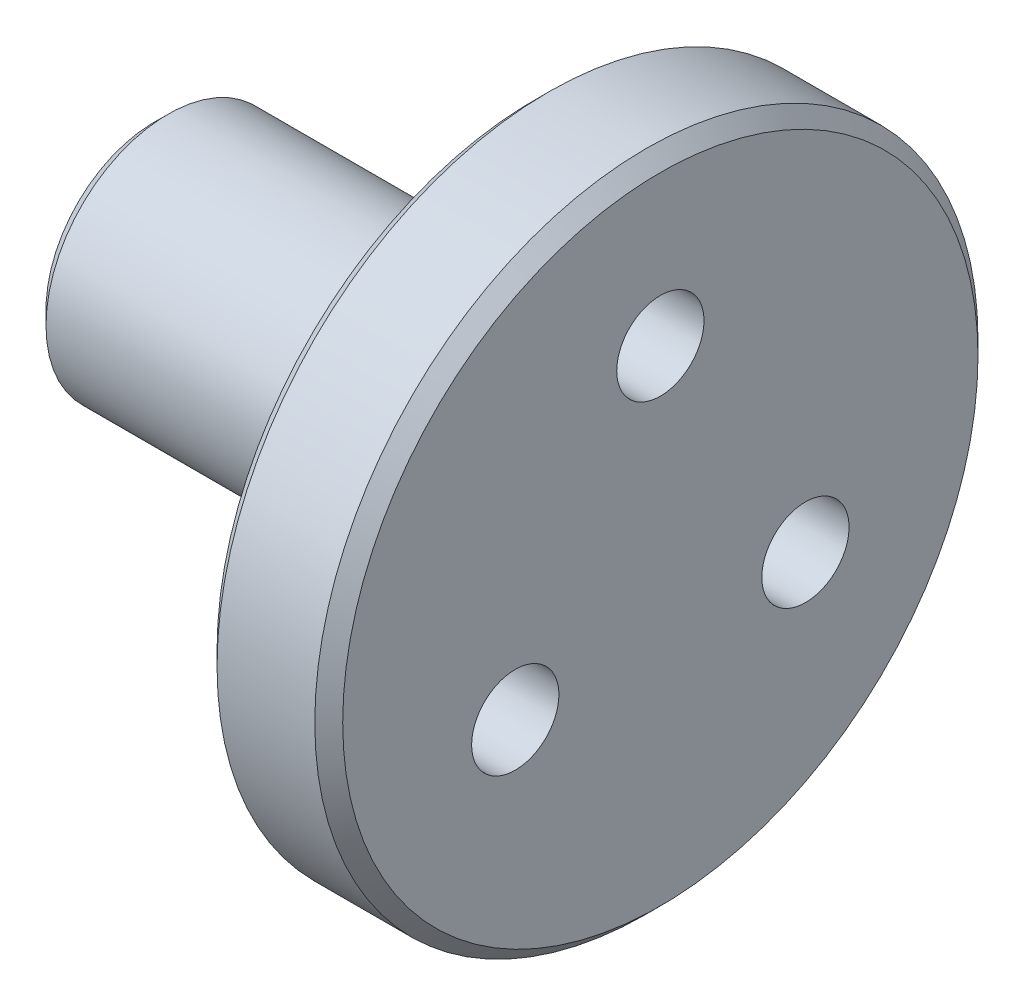
SolidWorks part; units mm, degrees
material "2024 Сплав"
ref_plane "Спереди" through (0, 0, 0) normal (0, 0, 1) x (1, 0, 0)
ref_plane "Сверху" through (0, 0, 0) normal (0, 1, 0) x (1, 0, 0)
ref_plane "Справа" through (0, 0, 0) normal (1, 0, 0) x (0, 0, -1)
sketch "Эскиз2" plane through (0, 0, 0) normal (0, 0, 1) x (1, 0, 0)
  line L0 (0, 0) -> (0, 9.5)
  line L1 (0, 9.5) -> (-3.6, 9.5)
  line L2 (-3.6, 9.5) -> (-3.6, 3.5)
  line L3 (-3.6, 3.5) -> (-14.5, 3.5)
  line L4 (-14.5, 3.5) -> (-14.5, 0)
  line L5 (-14.5, 0) -> (0, 0) construction
  line L6 (0, 0) -> (-14.5, 0)
  dimension "D1" = 10.9
  dimension "D2" = 14.5
  dimension "D3" = 3.5
  dimension "D4" = 9.5
revolve "Повернуть1" add sketch "Эскиз2" angle 360 about L5
sketch "Эскиз3" plane through (-3.6, 0, 0) normal (-1, 0, 0) x (0, 0, 1)
  circle A0 centre (0, 4.8) radius 1.25
  dimension "D1" = 2.5
  dimension "D2" = 4.8
extrude "Вырез-Вытянуть1" cut sketch "Эскиз3" against normal through all contours A0
chamfer "Фаска1" distance 0.4 angle 45 3 edges at (-14.5, 0, 3.5) (0, 0, 9.5) (-3.6, 0, 9.5)
pattern_circular "Круговой массив1" count 3 over 360 about axis through (0, 0, 0) along (1, 0, 0) of "Вырез-Вытянуть1"
